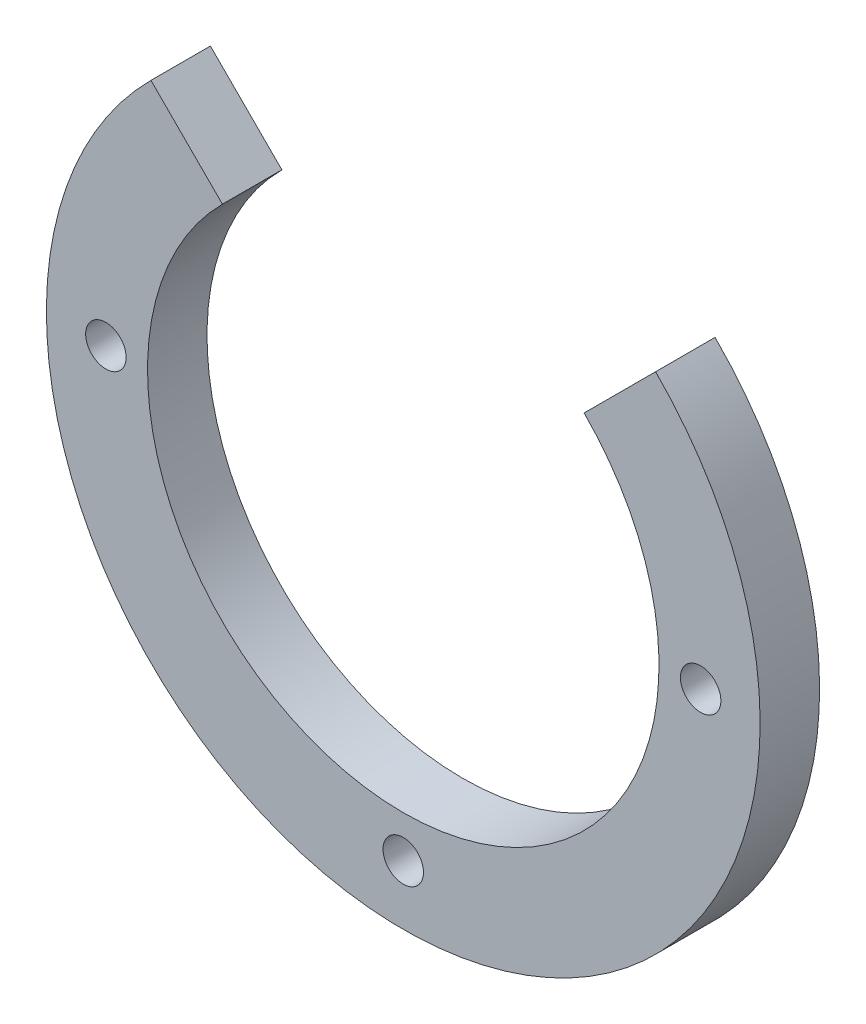
SolidWorks part; units mm, degrees
material "6061-T6 (SS)"
ref_plane "前视基准面" through (0, 0, 0) normal (0, 0, 1) x (1, 0, 0)
ref_plane "上视基准面" through (0, 0, 0) normal (0, 1, 0) x (1, 0, 0)
ref_plane "右视基准面" through (0, 0, 0) normal (1, 0, 0) x (0, 0, -1)
sketch "草图1" plane through (0, 0, 0) normal (0, 0, 1) x (1, 0, 0)
  circle A0 centre (0, 0) radius 30
  circle A1 centre (0, 0) radius 21.5
  dimension "D1" = 60
  dimension "D2" = 43
extrude "凸台-拉伸1" add sketch "草图1" along normal blind 5
sketch "草图2" plane through (0, 0, 5) normal (0, 0, 1) x (1, 0, 0)
  circle A0 centre (0, 0) radius 25 construction
  point P3 (-25, 0)
  point P4 (0, 25)
  point P5 (25, 0)
  point P6 (0, -25)
  dimension "D1" = 50
hole_wizard "Ø3.4 (3.4) 直径孔1" positions "3D草图1" profile "草图3" hole size "Ø3.4" standard "GB" end condition through all
sketch3d "3D草图1"
  point P0 (-25, 0, 5)
  point P3 (0, 25, 5)
  point P6 (0, -25, 5)
  point P9 (25, 0, 5)
sketch "草图3" plane through (-25, 0, 5) normal (1, 0, 0) x (0, -1, 0)
  line L0 (0, 0) -> (0, 5)
  line L1 (0, 5) -> (1.7, 5)
  line L2 (1.7, 5) -> (1.7, 0)
  line L5 (1.7, 0) -> (0, 0)
  line L11 (0, -6.35) -> (0, 107.95) construction
  dimension "通孔孔直径" = 3.4
  dimension "通孔孔深度" = 5
sketch "草图4" plane through (0, 0, 5) normal (0, 0, 1) x (1, 0, 0)
  line L0 (0, 0) -> (-21.2132, 21.2132)
  line L1 (21.2132, 21.2132) -> (0, 0)
  line L2 (-25, 0) -> (25, 0) construction
  arc A0 (21.2132, 21.2132) -> (-21.2132, 21.2132) centre (0, 0) ccw
  point P5 (-25, 0)
  dimension "D1" = 60
  dimension "D2" = 45
  dimension "D3" = 45
extrude "切除-拉伸1" cut sketch "草图4" against normal through all
